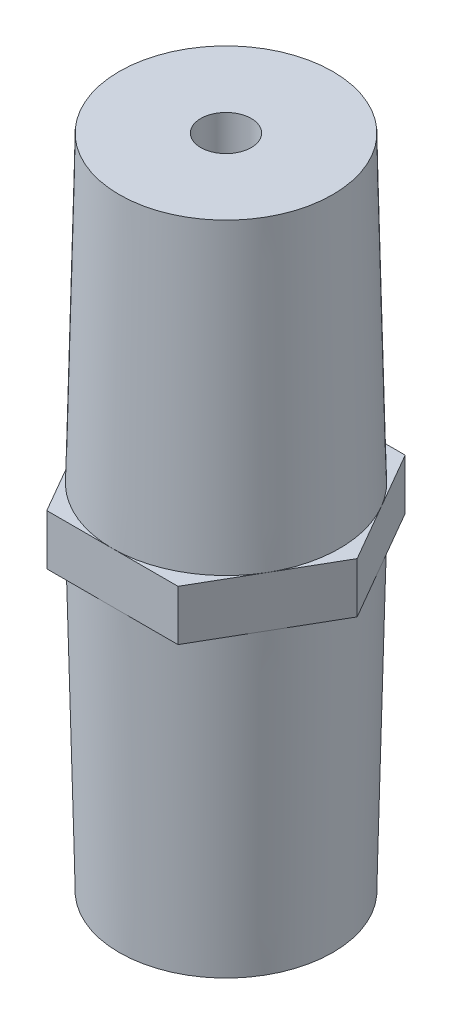
SolidWorks part; units mm, degrees
material "AISI 316 Annealed Stainless Steel Bar (SS)"
ref_plane "Front Plane" through (0, 0, 0) normal (0, 0, 1) x (1, 0, 0)
ref_plane "Top Plane" through (0, 0, 0) normal (0, 1, 0) x (1, 0, 0)
ref_plane "Right Plane" through (0, 0, 0) normal (1, 0, 0) x (0, 0, -1)
sketch "Sketch3" plane through (0, 0, 0) normal (0, 1, 0) x (1, 0, 0)
  line L1 (8.2489, 0) -> (4.1244, 7.1437)
  line L2 (4.1244, 7.1437) -> (-4.1244, 7.1437)
  line L3 (-4.1244, 7.1437) -> (-8.2489, 0)
  line L4 (-8.2489, 0) -> (-4.1244, -7.1437)
  line L5 (-4.1244, -7.1437) -> (4.1244, -7.1437)
  line L6 (4.1244, -7.1437) -> (8.2489, 0)
  circle A0 centre (0, 0) radius 7.1437 construction
  point P1 (0, 0)
  dimension "D1" = 14.2875
extrude "Boss-Extrude3" add sketch "Sketch3" along normal blind 1.5875
sketch "Sketch4" plane through (0, 1.5875, 0) normal (0, 1, 0) x (1, 0, 0)
  line L0 (-4.1244, 7.1437) -> (-8.2489, 0) construction
  circle A0 centre (0, 0) radius 7.1438
extrude "Boss-Extrude4" add sketch "Sketch4" along normal blind 19.05 draft 1.3
mirror "Mirror1" about plane through (0, 0, 0) normal (0, 1, 0) of "Boss-Extrude3", "Boss-Extrude4"
sketch "Sketch5" plane through (0, 20.6375, 0) normal (0, 1, 0) x (1, 0, 0)
  circle A0 centre (0, 0) radius 1.5875
  dimension "D1" = 3.175
extrude "Cut-Extrude1" cut sketch "Sketch5" against normal through all
